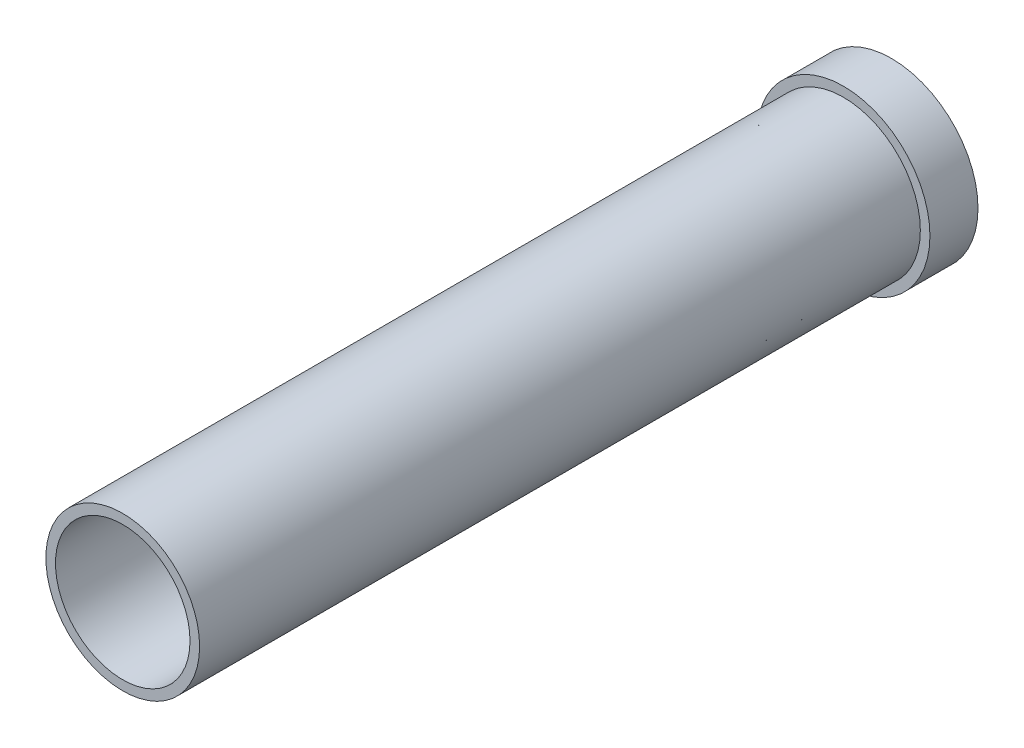
SolidWorks part; units mm, degrees
ref_plane "Piano frontale" through (0, 0, 0) normal (0, 0, 1) x (1, 0, 0)
ref_plane "Piano superiore" through (0, 0, 0) normal (0, 1, 0) x (1, 0, 0)
ref_plane "Piano destro" through (0, 0, 0) normal (1, 0, 0) x (0, 0, -1)
sketch "Schizzo1" plane through (0, 0, 0) normal (0, 0, 1) x (1, 0, 0)
  circle A0 centre (0, 0) radius 9.75
  circle A1 centre (0, 0) radius 7
extrude "Estrusione-Estrusione1" add sketch "Schizzo1" along normal blind 5 contours A0 | A1
sketch "Schizzo3" plane through (0, 0, 5) normal (0, 0, 1) x (1, 0, 0)
  circle A0 centre (0, 0) radius 8
  circle A1 centre (0, 0) radius 7
extrude "Estrusione-Estrusione2" add sketch "Schizzo3" along normal blind 75
chamfer "Smusso1" distance 2 angle 45 1 edges at (7, 0, 0)
sketch "Schizzo4" plane through (0, 0, 0) normal (0, 0, -1) x (-1, 0, 0)
  circle A0 centre (0, 0) radius 9
  circle A1 centre (0, 0) radius 9.75
extrude "Taglio-Estrusione1" cut sketch "Schizzo4" against normal blind 10
